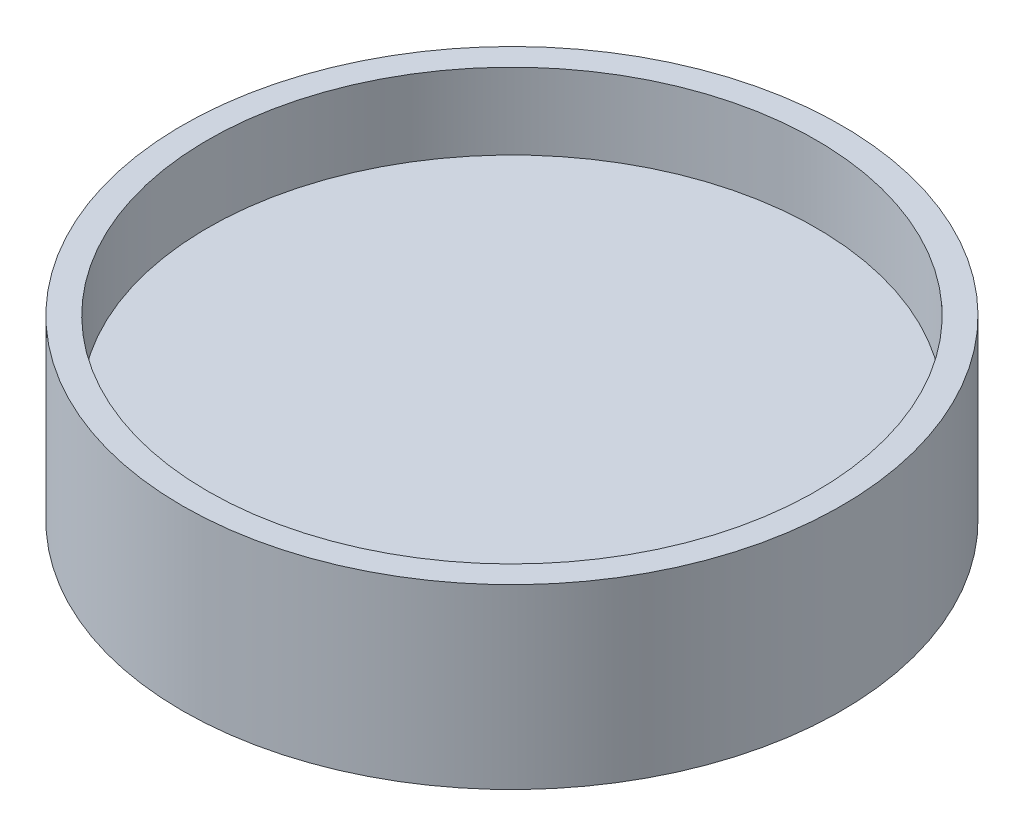
SolidWorks part; units mm, degrees
ref_plane "Front Plane" through (0, 0, 0) normal (0, 0, 1) x (1, 0, 0)
ref_plane "Top Plane" through (0, 0, 0) normal (0, 1, 0) x (1, 0, 0)
ref_plane "Right Plane" through (0, 0, 0) normal (1, 0, 0) x (0, 0, -1)
other "Configuration Table"
sketch "草图1" plane through (0, 0, 0) normal (0, 1, 0) x (1, 0, 0)
  circle A0 centre (0, 0) radius 13
  dimension "D1" = 26
extrude "凸台-拉伸1" add sketch "草图1" along normal blind 7
sketch "草图2" plane through (0, 7, 0) normal (0, 1, 0) x (1, 0, 0)
  circle A0 centre (0, 0) radius 12
  dimension "D1" = 24
extrude "切除-拉伸1" cut sketch "草图2" against normal blind 3
